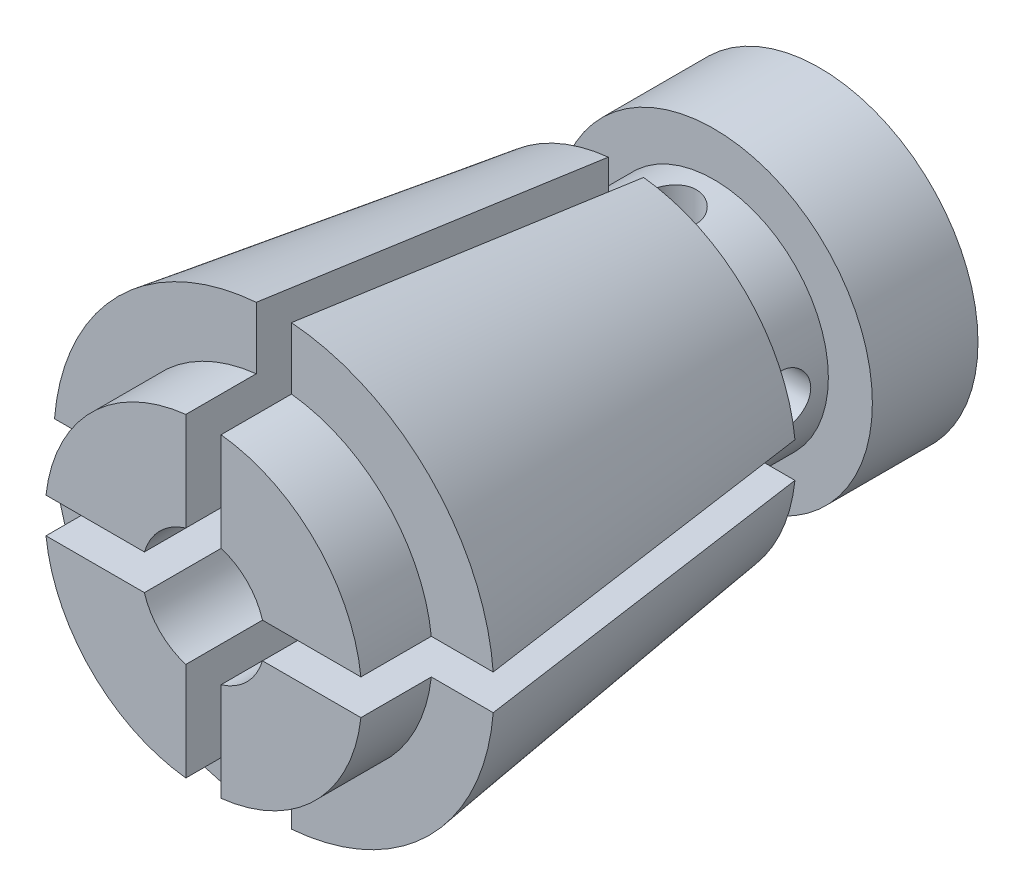
SolidWorks part; units mm, degrees
ref_plane "前视基准面" through (0, 0, 0) normal (0, 0, 1) x (1, 0, 0)
ref_plane "上视基准面" through (0, 0, 0) normal (0, 1, 0) x (1, 0, 0)
ref_plane "右视基准面" through (0, 0, 0) normal (1, 0, 0) x (0, 0, -1)
other "Configuration Table"
sketch "草图1" plane through (0, 0, 0) normal (1, 0, 0) x (0, 0, -1)
  line L0 (-115.126, 0) -> (90.9497, 0) construction
  line L1 (-2.5, 6.5) -> (2.5, 6.5)
  line L2 (2.5, 6.5) -> (2.5, 9)
  line L3 (2.5, 9) -> (8.5, 9)
  line L4 (8.5, 9) -> (8.5, 0)
  line L5 (-2.5, 6.5) -> (-2.5, 9.6536)
  line L6 (-2.5, 9.6536) -> (-22.5, 12.5)
  line L7 (-22.5, 12.5) -> (-22.5, 9)
  line L8 (-22.5, 9) -> (-26.5, 9)
  line L9 (-26.5, 9) -> (-26.5, 0)
  line L10 (8.5, 0) -> (-26.5, 0)
  point P6 (0, 6.5)
  point P14 (0, 0)
  dimension "D1" = 8.1
  dimension "D2" = 5
  dimension "D3" = 20
  dimension "D4" = 4
  dimension "D5" = 6
  dimension "D6" = 6.5
  dimension "D7" = 9
  dimension "D8" = 9
  dimension "D9" = 12.5
revolve "旋转1" add sketch "草图1" angle 360 about L0
sketch "草图2" plane through (0, 0, 0) normal (0, 1, 0) x (1, 0, 0)
  circle A0 centre (0, 0) radius 1.5
  dimension "D1" = 3
extrude "切除-拉伸1" cut sketch "草图2" against normal blind 10
pattern_circular "阵列(圆周)1" count 4 over 360 about axis through (0, 0, 2.5) along (0, 0, 1) of "切除-拉伸1"
sketch "草图3" plane through (0, 0, -8.5) normal (0, 0, -1) x (-1, 0, 0)
  circle A0 centre (0, 0) radius 3.5
  dimension "D1" = 7
extrude "切除-拉伸3" cut sketch "草图3" against normal up to surface (35.001 mm away)
sketch "草图4" plane through (0, 0, 26.5) normal (0, 0, 1) x (1, 0, 0)
  line L1 (-15.6839, 1) -> (15.6839, 1)
  line L2 (-15.6839, 1) -> (-15.6839, -1)
  line L3 (-15.6839, -1) -> (15.6839, -1)
  line L4 (15.6839, 1) -> (15.6839, -1)
  line L5 (-15.6839, 1) -> (15.6839, -1) construction
  line L6 (-15.6839, -1) -> (15.6839, 1) construction
  point P0 (0, 0)
  dimension "D1" = 2
extrude "切除-拉伸4" cut sketch "草图4" against normal up to surface (35.001 mm away)
sketch "草图5" plane through (0, 0, 26.5) normal (0, 0, 1) x (1, 0, 0)
  line L1 (-1, 14.2121) -> (1, 14.2121)
  line L2 (-1, 14.2121) -> (-1, -14.2121)
  line L3 (-1, -14.2121) -> (1, -14.2121)
  line L4 (1, 14.2121) -> (1, -14.2121)
  line L5 (-1, 14.2121) -> (1, -14.2121) construction
  line L6 (-1, -14.2121) -> (1, 14.2121) construction
  point P0 (0, 0)
  dimension "D1" = 2
extrude "切除-拉伸5" cut sketch "草图5" against normal up to surface (24 mm away)
